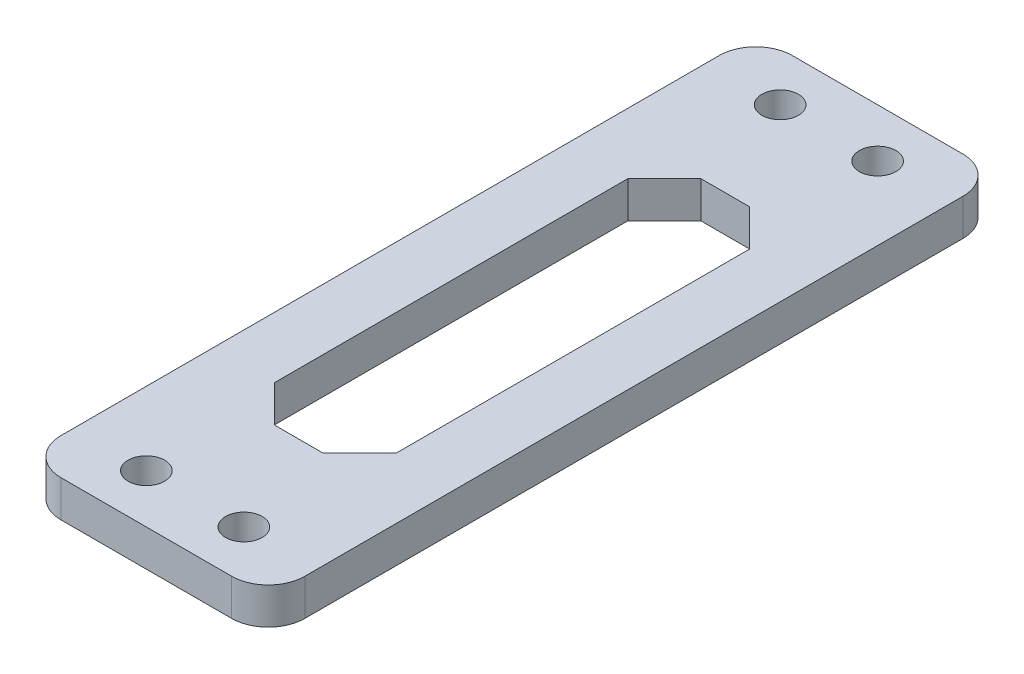
SolidWorks part; units mm, degrees
material "Thornel Mat VMA"
ref_plane "前视基准面" through (0, 0, 0) normal (0, 0, 1) x (1, 0, 0)
ref_plane "上视基准面" through (0, 0, 0) normal (0, 1, 0) x (1, 0, 0)
ref_plane "右视基准面" through (0, 0, 0) normal (1, 0, 0) x (0, 0, -1)
other "Configuration Table"
sketch "草图1" plane through (0, 0, 0) normal (0, 1, 0) x (1, 0, 0)
  line L0 (0, 0) -> (0, 41.7224) construction
  line L1 (-10, -30) -> (10, -30)
  line L2 (-10, -30) -> (-10, 30)
  line L3 (-10, 30) -> (10, 30)
  line L4 (10, -30) -> (10, 30)
  line L5 (-10, -30) -> (10, 30) construction
  line L6 (-10, 30) -> (10, -30) construction
  line L7 (0, 0) -> (20.4693, 0) construction
  line L9 (-5, -17.5) -> (5, -17.5)
  line L10 (-5, -17.5) -> (-5, 17.5)
  line L11 (-5, 17.5) -> (5, 17.5)
  line L12 (5, -17.5) -> (5, 17.5)
  line L13 (-5, -17.5) -> (5, 17.5) construction
  line L14 (-5, 17.5) -> (5, -17.5) construction
  circle A0 centre (-4, 26) radius 1.5
  circle A1 centre (4, 26) radius 1.5
  circle A2 centre (4, -26) radius 1.5
  circle A3 centre (-4, -26) radius 1.5
  point P0 (0, 0)
  dimension "D3" = 3
  dimension "D4" = 8
  dimension "D1" = 60
  dimension "D2" = 20
  dimension "D5" = 4
  dimension "D6" = 10
  dimension "D7" = 35
extrude "凸台-拉伸1" add sketch "草图1" along normal blind 3
chamfer "倒角1" distance 3 angle 45 4 edges at (5, 1.5, 17.5) (-5, 1.5, 17.5) (5, 1.5, -17.5) (-5, 1.5, -17.5)
fillet "圆角1" radius 3 4 edges at (-10, 1.5, 30) (10, 1.5, 30) (-10, 1.5, -30) (10, 1.5, -30)
